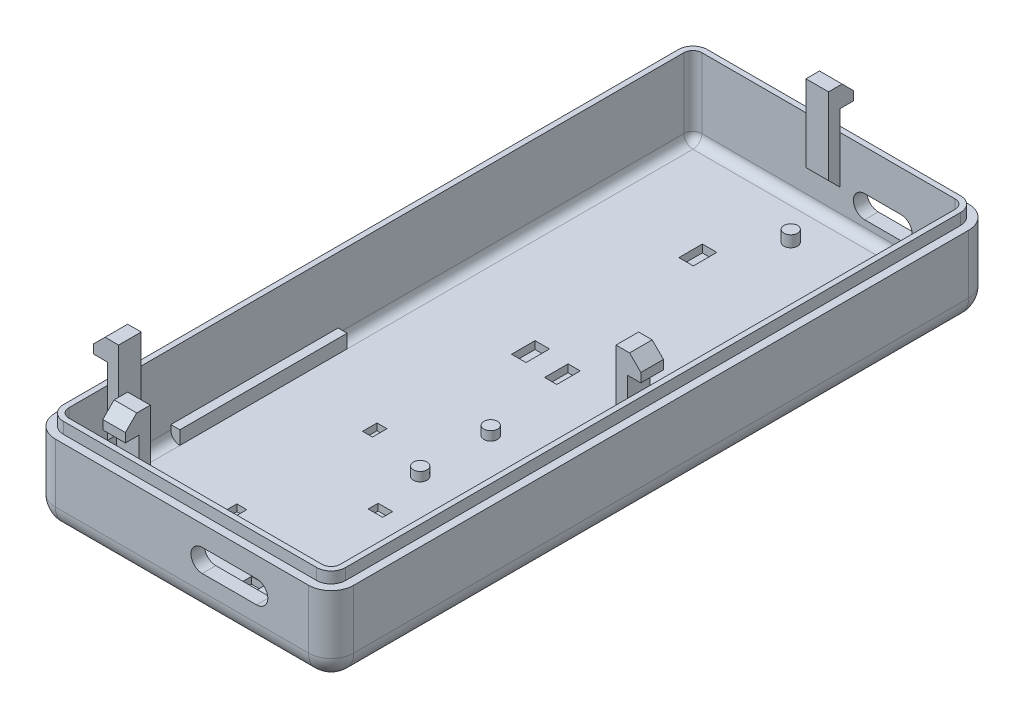
SolidWorks part; units mm, degrees
ref_plane "Plano frontal" through (0, 0, 0) normal (0, 0, 1) x (1, 0, 0)
ref_plane "Plano superior" through (0, 0, 0) normal (0, 1, 0) x (1, 0, 0)
ref_plane "Plano direito" through (0, 0, 0) normal (1, 0, 0) x (0, 0, -1)
sketch "Esboço2" plane through (0, 0, 0) normal (0, 1, 0) x (1, 0, 0)
  line L1 (30, -70) -> (-30, -70)
  line L2 (30, -70) -> (30, 70)
  line L3 (30, 70) -> (-30, 70)
  line L4 (-30, -70) -> (-30, 70)
  line L5 (30, -70) -> (-30, 70) construction
  line L6 (30, 70) -> (-30, -70) construction
  point P0 (0, 0)
  dimension "D1" = 140
  dimension "D2" = 60
extrude "Ressalto-extrusão1" add sketch "Esboço2" along normal blind 15
fillet "Filete2" radius 2 8 edges at (0, 0, -70) (-30, 7.5, -70) (-30, 0, 0) (30, 7.5, -70) (30, 0, 0) (0, 0, 70) (30, 7.5, 70) (-30, 7.5, 70)
shell "Casca3" thickness 3
sketch "Esboço3" plane through (0, 15, 0) normal (0, 1, 0) x (1, 0, 0)
  line L21 (30, -68) -> (30, 68) construction
  line L22 (-28, -70) -> (28, -70) construction
  line L23 (-30, 68) -> (-30, -68) construction
  line L24 (28, 70) -> (-28, 70) construction
  line L25 (31.2, -68) -> (31.2, 68)
  line L26 (-28, -71.2) -> (28, -71.2)
  line L27 (-31.2, 68) -> (-31.2, -68)
  line L28 (28, 71.2) -> (-28, 71.2)
  line L29 (31.2, -68) -> (31.2, 68)
  line L30 (-28, -71.2) -> (28, -71.2)
  line L31 (-31.2, 68) -> (-31.2, -68)
  line L32 (28, 71.2) -> (-28, 71.2)
  line L33 (30, -68) -> (30, 68)
  line L34 (-28, -70) -> (28, -70)
  line L35 (-30, 68) -> (-30, -68)
  line L36 (28, 70) -> (-28, 70)
  arc A16 (30, 68) -> (28, 70) centre (28, 68) ccw construction
  arc A17 (28, -70) -> (30, -68) centre (28, -68) ccw construction
  arc A18 (-30, -68) -> (-28, -70) centre (-28, -68) ccw construction
  arc A19 (-28, 70) -> (-30, 68) centre (-28, 68) ccw construction
  arc A20 (31.2, 68) -> (28, 71.2) centre (28, 68) ccw
  arc A21 (28, -71.2) -> (31.2, -68) centre (28, -68) ccw
  arc A22 (-31.2, -68) -> (-28, -71.2) centre (-28, -68) ccw
  arc A23 (-28, 71.2) -> (-31.2, 68) centre (-28, 68) ccw
  arc A24 (31.2, 68) -> (28, 71.2) centre (28, 68) ccw
  arc A25 (28, -71.2) -> (31.2, -68) centre (28, -68) ccw
  arc A26 (-31.2, -68) -> (-28, -71.2) centre (-28, -68) ccw
  arc A27 (-28, 71.2) -> (-31.2, 68) centre (-28, 68) ccw
  arc A28 (30, 68) -> (28, 70) centre (28, 68) ccw
  arc A29 (28, -70) -> (30, -68) centre (28, -68) ccw
  arc A30 (-30, -68) -> (-28, -70) centre (-28, -68) ccw
  arc A31 (-28, 70) -> (-30, 68) centre (-28, 68) ccw
  dimension "D1" = 1.2
extrude "Ressalto-extrusão2" add sketch "Esboço3" along normal blind 2.5
sketch "Esboço8" plane through (0, 0, 0) normal (0, 1, 0) x (1, 0, 0)
  line L3 (30, -68) -> (30, 68) construction
  line L5 (28, 70) -> (-28, 70) construction
  line L10 (23.1, 13) -> (23.1, 10.5)
  line L11 (23.1, 10.5) -> (25.6, 10.5)
  line L12 (25.6, 10.5) -> (25.6, 13)
  circle A0 centre (24.35, 61) radius 2.5
  arc A4 (25.6, 13) -> (23.1, 13) centre (24.35, 13) ccw
  dimension "D3" = 5
  dimension "D6" = 48
  dimension "D4" = 2.5
  dimension "D1" = 5.65
  dimension "D2" = 9
  dimension "D5" = 2.5
extrude "Ressalto-extrusão4" add sketch "Esboço8" along normal blind 10.5 separate body
sketch "Esboço10" plane through (0, 10.5, 0) normal (0, 1, 0) x (1, 0, 0)
  line L1 (25.6, 10.5) -> (25.6, 13) construction
  line L2 (23.1, 10.5) -> (25.6, 10.5) construction
  line L3 (23.1, 13) -> (23.1, 10.5) construction
  line L4 (25.6, 10.5) -> (25.6, 13)
  line L5 (23.1, 10.5) -> (25.6, 10.5)
  line L6 (23.1, 13) -> (23.1, 10.5)
  circle A4 centre (24.35, 61) radius 1.25
  arc A5 (23.1, 13) -> (25.6, 13) centre (24.35, 13) ccw
  circle A10 centre (24.35, 61) radius 2.5 construction
  circle A12 centre (24.35, 61) radius 2.5
extrude "Corte-extrusão3" cut sketch "Esboço10" against normal blind 3
sketch "Esboço11" plane through (0, 0, -73) normal (0, 0, -1) x (-1, 0, 0)
  line L0 (0, -3) -> (0, 15) construction
  line L1 (28, -3) -> (-28, -3) construction
  line L2 (-28, 15) -> (28, 15) construction
  line L3 (-8, 6) -> (-16, 6) construction
  line L8 (-8, 3.5) -> (-16, 3.5)
  line L9 (-8, 8.5) -> (-16, 8.5)
  arc A0 (-8, 3.5) -> (-8, 8.5) centre (-8, 6) ccw
  arc A1 (-16, 8.5) -> (-16, 3.5) centre (-16, 6) ccw
  point P8 (-12, 6)
  dimension "D1" = 9
  dimension "D2" = 5
  dimension "D3" = 8
  dimension "D4" = 12
extrude "Corte-extrusão2" cut sketch "Esboço11" against normal up to next (3 mm away)
sketch "Esboço15" plane through (0, 0, 73) normal (0, 0, 1) x (1, 0, 0)
  line L0 (0, -3) -> (0, 17.5) construction
  line L2 (16.5, 8) -> (4.5, 8) construction
  line L3 (16.5, 5.5) -> (4.5, 5.5)
  line L4 (16.5, 10.5) -> (4.5, 10.5)
  line L5 (28, -3) -> (-28, -3) construction
  line L6 (-28, 17.5) -> (28, 17.5) construction
  arc A0 (16.5, 5.5) -> (16.5, 10.5) centre (16.5, 8) ccw
  arc A1 (4.5, 10.5) -> (4.5, 5.5) centre (4.5, 8) ccw
  point P6 (10.5, 8)
  dimension "D1" = 5
  dimension "D2" = 11
  dimension "D3" = 12
  dimension "D4" = 10.5
extrude "Corte-extrusão4" cut sketch "Esboço15" against normal up to surface (3 mm away) up to face at (0, 9.75, 70)
sketch "Esboço12" plane through (0, 0, 0) normal (1, 0, 0) x (0, 0, -1)
  line L0 (0, 0) -> (0, -8) construction
  line L2 (68, -3) -> (-68, -3) construction
  line L3 (-10.5, -8) -> (0, -8)
  line L4 (-10.5, -8) -> (-15.5, -3)
  line L5 (-11.7426, -11) -> (0, -11)
  line L6 (-17.9142, -4.8284) -> (-11.7426, -11) construction
  line L7 (-15.7929, -2.7071) -> (-10.5, -8) construction
  line L8 (-11.7426, -11) -> (-19.7426, -3)
  line L9 (-19.7426, -3) -> (-15.5, -3)
  line L10 (19.7426, -3) -> (15.5, -3)
  line L11 (11.7426, -11) -> (19.7426, -3)
  line L12 (11.7426, -11) -> (0, -11)
  line L13 (10.5, -8) -> (15.5, -3)
  line L14 (10.5, -8) -> (0, -8)
  dimension "D1" = 5
  dimension "D2" = 3
  dimension "D3" = 135
  dimension "D4" = 3
  dimension "D5" = 10.5
extrude "Ressalto-extrusão6" add sketch "Esboço12" along normal mid plane 20
draft "Inclinação2" type of draft neutral plane draft angle 10 faces to draft 2 face at (-10, -6.25, 0) face at (10, -6.25, 0) neutral plane through (10, -11, -11.7426) neutral plane normal (0, -1, 0) parameters "D1"=10
sketch "Esboço27" plane through (0, 0, 0) normal (0, 1, 0) x (1, 0, 0)
  line L0 (0, 0) -> (-30, 0) construction
  line L6 (-30, 68) -> (-30, -68) construction
  line L7 (-28.0011, -8.4567) -> (-30, -8.4567)
  line L8 (-28.0011, -8.4567) -> (-28.0011, -45.4567)
  line L9 (-28.0011, -45.4567) -> (-30, -45.4567)
  line L10 (-30, -8.4567) -> (-30, -45.4567)
  line L11 (-28.0011, -8.4567) -> (-30, -45.4567) construction
  line L12 (-28.0011, -45.4567) -> (-30, -8.4567) construction
  line L13 (30, -68) -> (30, 68) construction
  line L14 (26.3943, -62.2655) -> (30, -62.2655)
  line L15 (26.3943, -62.2655) -> (26.3943, -37.1362)
  line L16 (26.3943, -37.1362) -> (30, -37.1362)
  line L17 (30, -62.2655) -> (30, -37.1362)
  line L18 (26.3943, -62.2655) -> (30, -37.1362) construction
  line L19 (26.3943, -37.1362) -> (30, -62.2655) construction
  point P2 (28.1972, -49.7009)
  point P12 (-29.0005, -26.9567)
  dimension "D1" = 26.9567
  dimension "D2" = 37
  dimension "D3" = 1.9989
  dimension "D4" = 49.7009
  dimension "D5" = 25.1294
  dimension "D6" = 3.6057
extrude "Ressalto-extrusão17" add sketch "Esboço27" along normal blind 3
sketch "Esboço28" plane through (0, 0, 0) normal (0, 1, 0) x (1, 0, 0)
  line L1 (-8.3057, -22.5509) -> (-10.5057, -22.5509)
  line L2 (-8.3057, -22.5509) -> (-8.3057, -19.3509)
  line L3 (-8.3057, -19.3509) -> (-10.5057, -19.3509)
  line L4 (-10.5057, -22.5509) -> (-10.5057, -19.3509)
  line L5 (-8.3057, -22.5509) -> (-10.5057, -19.3509) construction
  line L6 (-8.3057, -19.3509) -> (-10.5057, -22.5509) construction
  line L7 (-30, 68) -> (-30, -68) construction
  line L8 (-28, -70) -> (28, -70) construction
  line L9 (-8.3057, -53.5509) -> (-10.5057, -53.5509)
  line L10 (-8.3057, -53.5509) -> (-8.3057, -50.3509)
  line L11 (-8.3057, -50.3509) -> (-10.5057, -50.3509)
  line L12 (-10.5057, -53.5509) -> (-10.5057, -50.3509)
  line L13 (-8.3057, -53.5509) -> (-10.5057, -50.3509) construction
  line L14 (-8.3057, -50.3509) -> (-10.5057, -53.5509) construction
  line L18 (-30, -45.4567) -> (-30, -68) construction
  line L19 (8.1943, -64.8009) -> (4.9943, -64.8009)
  line L20 (8.1943, -64.8009) -> (8.1943, -62.6009)
  line L21 (8.1943, -62.6009) -> (4.9943, -62.6009)
  line L22 (4.9943, -64.8009) -> (4.9943, -62.6009)
  line L23 (8.1943, -64.8009) -> (4.9943, -62.6009) construction
  line L24 (8.1943, -62.6009) -> (4.9943, -64.8009) construction
  line L26 (-28, -70) -> (28, -70) construction
  line L27 (4.9943, -34.6009) -> (8.1943, -34.6009)
  line L28 (4.9943, -34.6009) -> (4.9943, -36.8009)
  line L29 (4.9943, -36.8009) -> (8.1943, -36.8009)
  line L30 (8.1943, -34.6009) -> (8.1943, -36.8009)
  line L31 (4.9943, -34.6009) -> (8.1943, -36.8009) construction
  line L32 (4.9943, -36.8009) -> (8.1943, -34.6009) construction
  point P0 (-9.4057, -20.9509)
  point P11 (6.5943, -63.7009)
  point P12 (-9.4057, -51.9509)
  point P31 (6.5943, -35.7009)
  dimension "D2" = 18.0491
  dimension "D3" = 2.2
  dimension "D4" = 3.2
  dimension "D5" = 2.2
  dimension "D6" = 31
  dimension "D7" = 3.2
  dimension "D8" = 2.2
  dimension "D9" = 2.2
  dimension "D10" = 3.2
  dimension "D11" = 20.5943
  dimension "D12" = 36.5943
  dimension "D13" = 6.2991
  dimension "D14" = 28
  dimension "D15" = 3.2
extrude "Corte-extrusão5" cut sketch "Esboço28" against normal blind 1.5
sketch "Esboço29" plane through (0, 0, 0) normal (0, 1, 0) x (1, 0, 0)
  line L1 (-5.6, 8.7) -> (-8.8, 8.7)
  line L2 (-5.6, 8.7) -> (-5.6, 13.9)
  line L3 (-5.6, 13.9) -> (-8.8, 13.9)
  line L4 (-8.8, 8.7) -> (-8.8, 13.9)
  line L5 (-5.6, 8.7) -> (-8.8, 13.9) construction
  line L6 (-5.6, 13.9) -> (-8.8, 8.7) construction
  line L7 (-5.6, 45.7) -> (-8.8, 45.7)
  line L8 (-5.6, 45.7) -> (-5.6, 50.9)
  line L9 (-5.6, 50.9) -> (-8.8, 50.9)
  line L10 (-8.8, 45.7) -> (-8.8, 50.9)
  line L11 (-5.6, 45.7) -> (-8.8, 50.9) construction
  line L12 (-5.6, 50.9) -> (-8.8, 45.7) construction
  line L19 (28, 70) -> (-28, 70) construction
  line L20 (-30, 68) -> (-30, -68) construction
  point P6 (-7.2, 11.3)
  point P12 (-7.2, 48.3)
  point P21 (-7.2, 48.3)
  dimension "D1" = 21.7
  dimension "D2" = 5.2
  dimension "D3" = 3.2
  dimension "D4" = 22.8
  dimension "D5" = 5.2
  dimension "D6" = 3.2
  dimension "D7" = 37
extrude "Corte-extrusão6" cut sketch "Esboço29" against normal blind 1.7
sketch "Esboço30" plane through (0, 0, 0) normal (0, 1, 0) x (1, 0, 0)
  line L0 (0, 0) -> (30, 0) construction
  line L3 (30, -68) -> (30, 68) construction
  line L7 (0, 0) -> (0, -70) construction
  line L8 (-28, -70) -> (28, -70) construction
  circle A0 centre (4.5, -24.8) radius 1.5
  circle A1 centre (4.5, -9.2) radius 1.5
  circle A2 centre (21.5, -9.2) radius 1.5
  circle A3 centre (21.5, -24.8) radius 1.5
  dimension "D1" = 3
  dimension "D2" = 4.5
  dimension "D3" = 17
  dimension "D4" = 15.6
  dimension "D5" = 9.2
extrude "Ressalto-extrusão18" add sketch "Esboço30" along normal blind 2
sketch "Esboço31" plane through (0, 0, 0) normal (0, 1, 0) x (1, 0, 0)
  line L0 (28, 70) -> (-28, 70) construction
  line L1 (30, -37.1362) -> (30, 68) construction
  circle A0 centre (0.65, 61) radius 1.5
  circle A1 centre (23.35, 61) radius 1.5
  dimension "D1" = 3
  dimension "D2" = 9
  dimension "D3" = 29.35
  dimension "D4" = 22.7
extrude "Ressalto-extrusão19" add sketch "Esboço31" along normal blind 2.5
sketch "Esboço32" plane through (0, 0, 0) normal (0, 1, 0) x (1, 0, 0)
  line L3 (30, -37.1362) -> (30, 68) construction
  line L5 (-0.6, 13) -> (-0.6, 8) construction
  line L6 (-0.6, 8) -> (1.9, 8) construction
  line L7 (-0.6, 13) -> (1.9, 13) construction
  line L8 (1.9, 13) -> (1.9, 8) construction
  line L9 (24.6, 13) -> (24.6, 8) construction
  line L10 (24.6, 8) -> (22.1, 8) construction
  line L11 (24.6, 13) -> (22.1, 13) construction
  line L12 (22.1, 13) -> (22.1, 8) construction
  line L14 (0, 0) -> (30, 0) construction
  line L15 (30, -68) -> (30, 68) construction
  line L16 (-0.7, 13.1) -> (-0.7, 7.9)
  line L17 (-0.7, 7.9) -> (2, 7.9)
  line L18 (2, 13.1) -> (2, 7.9)
  line L19 (-0.7, 13.1) -> (2, 13.1)
  line L20 (24.7, 13.1) -> (24.7, 7.9)
  line L21 (24.7, 7.9) -> (22, 7.9)
  line L22 (22, 13.1) -> (22, 7.9)
  line L23 (24.7, 13.1) -> (22, 13.1)
  circle A1 centre (0.65, 13) radius 1.25 construction
  dimension "D1" = 5.4
  dimension "D2" = 20.2
  dimension "D3" = 2.5
  dimension "D4" = 8
  dimension "D5" = 5
  dimension "D6" = 2.5
  dimension "D7" = 0.1
extrude "Corte-extrusão7" cut sketch "Esboço32" against normal blind 1.7
ref_plane "Plano1" through (0, 0, 57) normal (0, 0, -1) x (-1, 0, 0)
ref_plane "Plano2" through (-15, 0, 0) normal (-1, 0, 0) x (0, 0, 1)
ref_plane "Plano3" through (0, 0, 2) normal (0, 0, 1) x (1, 0, 0)
sketch "Esboço34" plane through (0, 0, 57) normal (0, 0, -1) x (-1, 0, 0)
  line L0 (30, 7) -> (30, 22)
  line L1 (30, 2) -> (30, 17.5) construction
  line L2 (30, 22) -> (33, 22)
  line L3 (33, 22) -> (33, 24)
  line L4 (30, 7) -> (27.5, 9.5)
  line L5 (27.5, 9.5) -> (27.5, 26.5)
  line L6 (27.5, 26.5) -> (30.5, 26.5)
  line L7 (30.5, 26.5) -> (33, 24)
  line L8 (33, 15) -> (28, 15) construction
  dimension "D1" = 45
  dimension "D2" = 2.5
  dimension "D3" = 8
  dimension "D4" = 15
  dimension "D5" = 5.5
  dimension "D6" = 2
  dimension "D7" = 135
  dimension "D8" = 3
extrude "Ressalto-extrusão20" add sketch "Esboço34" along normal mid plane 5
sketch "Esboço35" plane through (-15, 0, 0) normal (-1, 0, 0) x (0, 0, 1)
  line L0 (70, 7) -> (70, 22)
  line L1 (70, 2) -> (70, 17.5) construction
  line L2 (70, 18.1) -> (70, 31.1) construction
  line L3 (70, 22) -> (73, 22)
  line L4 (73, 22) -> (73, 24)
  line L5 (73, 24) -> (70.5, 26.5)
  line L6 (70.5, 26.5) -> (67.5, 26.5)
  line L7 (67.5, 26.5) -> (67.5, 9.5)
  line L8 (67.5, 9.5) -> (70, 7)
  line L9 (73, 15) -> (68, 15) construction
  dimension "D1" = 45
  dimension "D2" = 135
  dimension "D3" = 2.5
  dimension "D4" = 8
  dimension "D5" = 15
  dimension "D6" = 5.5
  dimension "D7" = 3
  dimension "D8" = 2
extrude "Ressalto-extrusão21" add sketch "Esboço35" along normal mid plane 5
sketch "Esboço36" plane through (0, 0, 2) normal (0, 0, 1) x (1, 0, 0)
  line L0 (30, 7) -> (30, 22)
  line L1 (30, 2) -> (30, 17.5) construction
  line L2 (30, 18.1) -> (30, 31.1) construction
  line L3 (30, 22) -> (33, 22)
  line L4 (33, 22) -> (33, 24)
  line L5 (33, 24) -> (30.5, 26.5)
  line L6 (30.5, 26.5) -> (27.5, 26.5)
  line L7 (27.5, 26.5) -> (27.5, 9.5)
  line L8 (27.5, 9.5) -> (30, 7)
  line L9 (33, 15) -> (28, 15) construction
  dimension "D1" = 45
  dimension "D2" = 8
  dimension "D3" = 2.5
  dimension "D4" = 15
  dimension "D5" = 2
  dimension "D6" = 135
  dimension "D7" = 5.5
  dimension "D8" = 3
extrude "Ressalto-extrusão22" add sketch "Esboço36" along normal mid plane 5
sketch "Esboço37" plane through (0, 0, 0) normal (1, 0, 0) x (0, 0, -1)
  line L0 (70, 7) -> (70, 22)
  line L1 (70, 2) -> (70, 17.5) construction
  line L2 (70, 18.1) -> (70, 31.1) construction
  line L3 (70, 22) -> (73, 22)
  line L4 (73, 22) -> (73, 24)
  line L5 (73, 24) -> (70.5, 26.5)
  line L6 (70.5, 26.5) -> (67.5, 26.5)
  line L7 (67.5, 26.5) -> (67.5, 9.5)
  line L8 (67.5, 9.5) -> (70, 7)
  line L9 (73, 15) -> (68, 15) construction
  dimension "D1" = 45
  dimension "D2" = 8
  dimension "D3" = 15
  dimension "D4" = 2.5
  dimension "D5" = 5.5
  dimension "D6" = 135
  dimension "D7" = 2
  dimension "D8" = 3
extrude "Ressalto-extrusão23" add sketch "Esboço37" along normal mid plane 5
